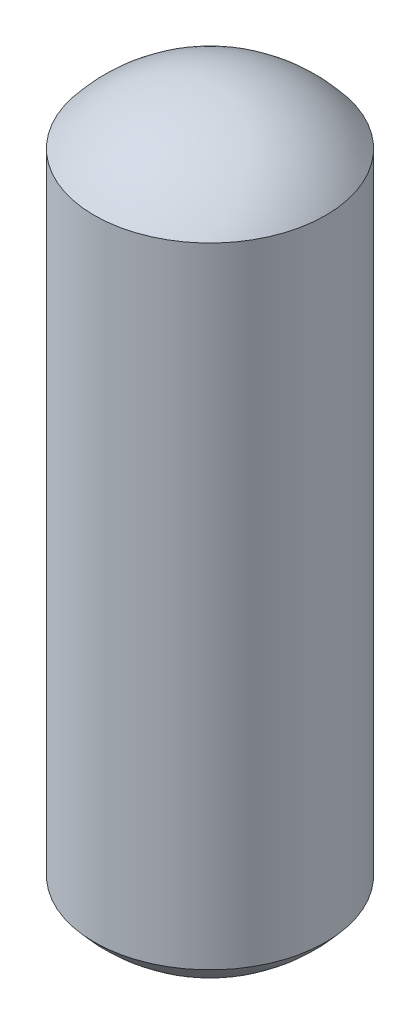
SolidWorks part; units mm, degrees
material "Plain Carbon Steel"
ref_plane "Front Plane" through (0, 0, 0) normal (0, 0, 1) x (1, 0, 0)
ref_plane "Top Plane" through (0, 0, 0) normal (0, 1, 0) x (1, 0, 0)
ref_plane "Right Plane" through (0, 0, 0) normal (1, 0, 0) x (0, 0, -1)
other "Configuration Table"
sketch "Sketch1" plane through (0, 0, 0) normal (0, 0, 1) x (1, 0, 0)
  line L0 (0, 5) -> (0, -21) construction
  line L1 (2.5, -1.2) -> (-2.5, -1.2) construction
  line L2 (2.5, -1.2) -> (2.5, -14.8)
  line L3 (2.5, -14.8) -> (-2.5, -14.8) construction
  line L4 (2.5, -16) -> (-2.5, -16) construction
  line L5 (0, -16) -> (0, 0)
  arc A0 (0, 0) -> (2.5, -1.2) centre (0, -3.2042) cw
  arc A1 (-2.5, -1.2) -> (0, 0) centre (0, -3.2042) cw construction
  arc A2 (2.5, -14.8) -> (0, -16) centre (0, -12.7958) cw
  arc A3 (0, -16) -> (-2.5, -14.8) centre (0, -12.7958) cw construction
  dimension "D1" = 1.2
  dimension "D2" = 5
  dimension "D3" = 1.2
  dimension "D4" = 5
  dimension "D5" = 5
  dimension "Length" = 16
revolve "Revolve1" add sketch "Sketch1" angle 360 about L0
